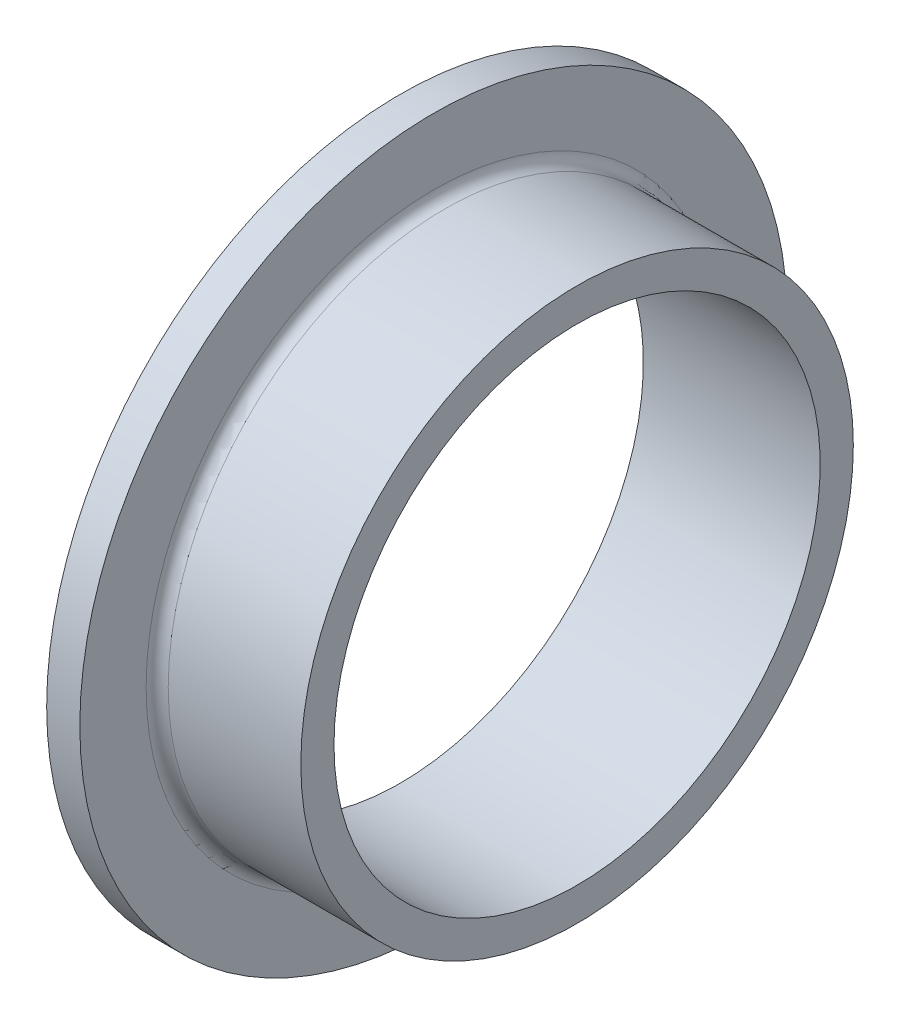
SolidWorks part; units mm, degrees
material "PPS"
ref_plane "Front Plane" through (0, 0, 0) normal (0, 0, 1) x (1, 0, 0)
ref_plane "Top Plane" through (0, 0, 0) normal (0, 1, 0) x (1, 0, 0)
ref_plane "Right Plane" through (0, 0, 0) normal (1, 0, 0) x (0, 0, -1)
sketch "Sketch1" plane through (0, 0, 0) normal (0, 0, 1) x (1, 0, 0)
  line L0 (0, 11) -> (0, 16)
  line L1 (0, 16) -> (1.5, 16)
  line L2 (1.5, 16) -> (1.5, 12.5)
  line L3 (1.5, 12.5) -> (8, 12.5)
  line L4 (8, 12.5) -> (8, 11)
  line L5 (8, 11) -> (0, 11)
  line L6 (0, 0) -> (22, 0) construction
  dimension "D1" = 11
  dimension "D2" = 8
  dimension "D3" = 1.5
  dimension "D4" = 12.5
  dimension "D5" = 16
revolve "Revolve1" add sketch "Sketch1" angle 360 about L6
fillet "Fillet1" radius 0.5 1 edges at (1.5, 0, 12.5)
